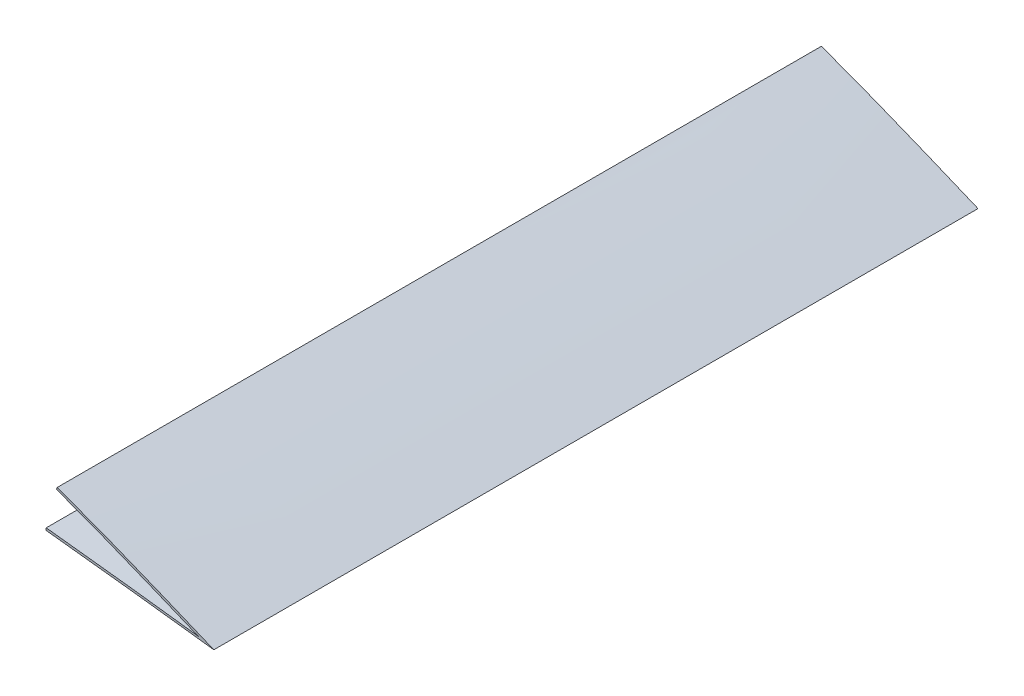
SolidWorks part; units mm, degrees
ref_plane "Front Plane" through (0, 0, 0) normal (0, 0, 1) x (1, 0, 0)
ref_plane "Top Plane" through (0, 0, 0) normal (0, 1, 0) x (1, 0, 0)
ref_plane "Right Plane" through (0, 0, 0) normal (1, 0, 0) x (0, 0, -1)
curve "ImportedCurve1"
curve "ImportedCurve2"
curve "ImportedCurve3"
curve "ImportedCurve4"
curve "ImportedCurve5"
curve "ImportedCurve6"
sketch "Sketch2" plane through (0, 0, 0) normal (0, 0, 1) x (1, 0, 0)
  line L0 (1990.4215, 2953.4976) -> (1990.598, 2953.971) construction
  line L1 (1988.0746, 2944.7099) -> (1988.0231, 2944.186) construction
  line L2 (1990.4215, 2953.4976) -> (1990.598, 2953.971)
  line L3 (1988.0746, 2944.7099) -> (1988.0231, 2944.186)
  spline S0 degree 3 poles (2134.4722, 5937.7504) (1873.7984, 2921.1769) (1934.682, 2950.5189) (1992.8786, 2943.6519) (1996.2606, 2943.2782) (1999.5028, 2942.8814) (2002.5951, 2942.5882) (2005.5143, 2942.1987) (2008.2863, 2941.9286) (2010.8855, 2941.5691) (2013.3339, 2941.2998) (2015.6079, 2941.0333) (2017.7058, 2940.7551) (2019.6294, 2940.5785) (2021.3677, 2940.3148) (2022.9312, 2940.1475) (2024.3197, 2939.9779) (2040.9017, 2937.5136) (2060.2366, 2960.4794) (1677.969, -39.4109) knots 21.840262 21.840262 21.840262 21.840262 28.487933 28.626756 28.761203 28.889816 29.012534 29.128022 29.237609 29.341434 29.437893 29.528519 29.611854 29.687831 29.75659 29.819438 29.873537 29.921805 31.799003 31.799003 31.799003 31.799003 only from (1988.0231, 2944.186) to (2026.3781, 2939.726) construction
  spline S1 degree 3 poles (233.2951, 540.7842) (2190.7322, 2909.2966) (2096.1539, 2911.6204) (2024.5633, 2940.4512) (2024.2524, 2940.5764) (2023.9421, 2940.702) (2023.6323, 2940.8284) (2019.9229, 2942.3416) (2016.3, 2943.9544) (2008.8404, 2946.8849) (2005.182, 2948.446) (1998.4983, 2950.9926) (1995.5753, 2952.1437) (1910.4781, 2983.2395) (1850.8895, 3056.3249) (615.8753, 294.7988) knots -8.9025 -8.9025 -8.9025 -8.9025 0.175577 0.175577 0.175577 0.214991 0.214991 0.214991 0.686933 0.686933 1.158874 1.158874 1.531655 1.531655 11.844812 11.844812 11.844812 11.844812 only from (2026.3781, 2939.726) to (1990.598, 2953.971) construction
  spline S2 degree 3 poles (-975.9261, 3003.4703) (2158.7311, 2891.9479) (2072.1047, 2920.1924) (2015.2173, 2943.7878) (2010.8021, 2945.5756) (2001.8663, 2949.1968) (1997.4462, 2950.8924) (1850.1304, 3005.5181) (1713.7064, 3065.7603) (153.1073, 605.8614) knots -6.327853 -6.327853 -6.327853 -6.327853 0.376825 0.376825 0.943228 0.943228 1.509632 1.509632 19.523491 19.523491 19.523491 19.523491 only from (2022.8665, 2940.6146) to (1990.4215, 2953.4976) construction
  spline S3 degree 3 poles (489.8915, 5492.5431) (1512.5621, 2879.1254) (1751.7363, 2971.7727) (1998.0522, 2943.5758) (2004.5957, 2942.8668) (2113.5456, 2929.4587) (2189.9897, 2892.3795) (4481.4364, 4652.5748) knots 0.087148 0.087148 0.087148 0.087148 28.56999 28.56999 29.343341 29.343341 41.606171 41.606171 41.606171 41.606171 only from (1988.0746, 2944.7099) to (2022.8665, 2940.6146) construction
  spline S4 degree 3 poles (1988.0231, 2944.186) (1988.4861, 2944.1404) (1990.1186, 2943.9776) (1992.8786, 2943.6519) (1996.2606, 2943.2782) (1999.5028, 2942.8814) (2002.5951, 2942.5882) (2005.5143, 2942.1987) (2008.2863, 2941.9286) (2010.8855, 2941.5691) (2013.3339, 2941.2998) (2015.6079, 2941.0333) (2017.7058, 2940.7551) (2019.6294, 2940.5785) (2021.3677, 2940.3148) (2022.9312, 2940.1475) (2024.3197, 2939.9779) (2025.4405, 2939.8113) (2026.1137, 2939.7556) (2026.3781, 2939.726) knots 28.432981 28.432981 28.432981 28.432981 28.487933 28.626756 28.761203 28.889816 29.012534 29.128022 29.237609 29.341434 29.437893 29.528519 29.611854 29.687831 29.75659 29.819438 29.873537 29.921805 29.95324 29.95324 29.95324 29.95324
  spline S5 degree 3 poles (2026.3781, 2939.726) (2025.7724, 2939.9668) (2025.167, 2940.2081) (2024.5633, 2940.4512) (2024.2524, 2940.5764) (2023.9421, 2940.702) (2023.6323, 2940.8284) (2019.9229, 2942.3416) (2016.3, 2943.9544) (2008.8404, 2946.8849) (2005.182, 2948.446) (1998.4983, 2950.9926) (1995.5753, 2952.1437) (1991.9359, 2953.4736) (1991.2665, 2953.7216) (1990.598, 2953.971) knots 0.099021 0.099021 0.099021 0.099021 0.175577 0.175577 0.175577 0.214991 0.214991 0.214991 0.686933 0.686933 1.158874 1.158874 1.531655 1.531655 1.615896 1.615896 1.615896 1.615896
  spline S6 degree 3 poles (2022.8665, 2940.6146) (2021.798, 2941.0615) (2020.7163, 2941.507) (2015.2173, 2943.7878) (2010.8021, 2945.5756) (2001.8663, 2949.1968) (1997.4462, 2950.8924) (1992.1106, 2952.8708) (1991.2661, 2953.1843) (1990.4215, 2953.4976) knots 0.240373 0.240373 0.240373 0.240373 0.376825 0.376825 0.943228 0.943228 1.509632 1.509632 1.616177 1.616177 1.616177 1.616177
  spline S7 degree 3 poles (1988.0746, 2944.7099) (1989.2302, 2944.5829) (1990.3856, 2944.4534) (1998.0522, 2943.5758) (2004.5957, 2942.8668) (2014.9909, 2941.5875) (2018.8846, 2941.0676) (2022.8665, 2940.6146) knots 28.432747 28.432747 28.432747 28.432747 28.56999 28.56999 29.343341 29.343341 29.813814 29.813814 29.813814 29.813814
extrude "Boss-Extrude1" add sketch "Sketch2" along normal blind 174.625
